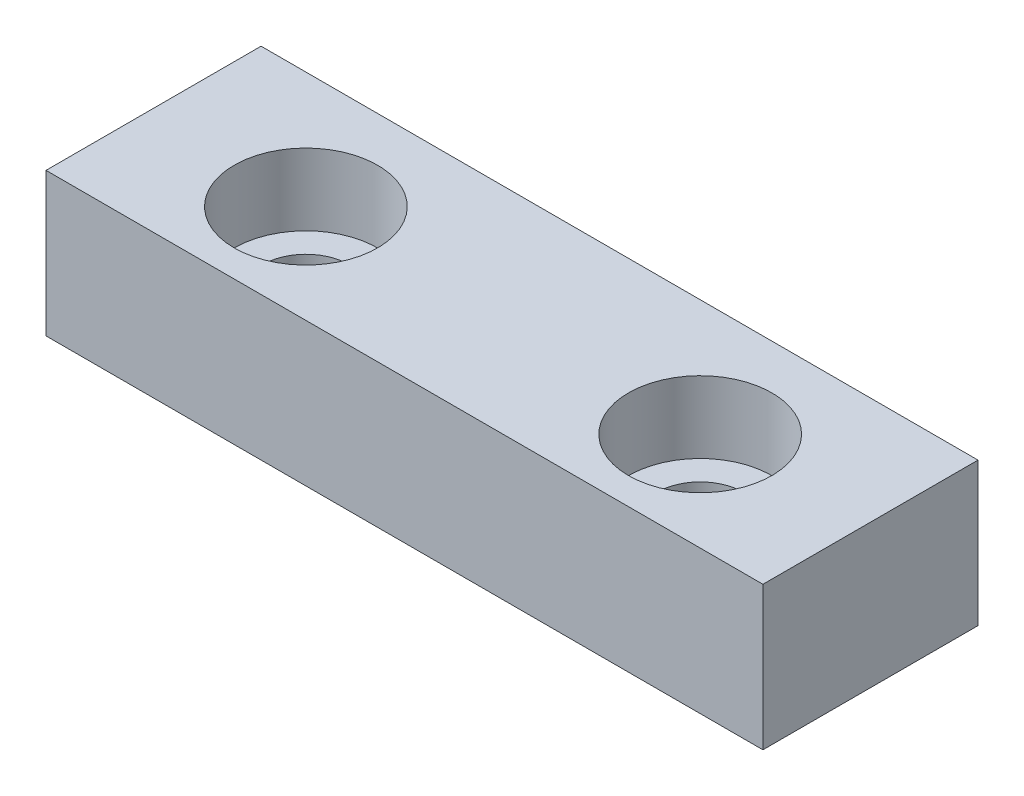
SolidWorks part; units mm, degrees
material "SKD11淬火HRC56-60"
ref_plane "前基準面" through (0, 0, 0) normal (0, 0, 1) x (1, 0, 0)
ref_plane "上基準面" through (0, 0, 0) normal (0, 1, 0) x (1, 0, 0)
ref_plane "右基準面" through (0, 0, 0) normal (1, 0, 0) x (0, 0, -1)
sketch "草图1" plane through (0, 0, 0) normal (0, 0, 1) x (1, 0, 0)
  line L1 (0, 0) -> (40, 0)
  line L2 (0, 0) -> (0, 8)
  line L3 (0, 8) -> (40, 8)
  line L4 (40, 0) -> (40, 8)
  dimension "D1" = 8
  dimension "D2" = 40
extrude "凸台-拉伸1" add sketch "草图1" along normal blind 12
hole_wizard "M4 六角凹头螺钉的柱形沉头孔3" positions "草图3" profile "草图2" counterbore size "M4" standard "ISO" end condition through all
sketch "草图3" plane through (0, 8, 0) normal (0, 1, 0) x (-1, 0, 0)
  line L0 (0, 6) -> (-40, 6) construction
  line L1 (0, 12) -> (0, 0) construction
  line L2 (-40, 12) -> (-40, 0) construction
  line L3 (-20, 0) -> (-20, 12) construction
  line L4 (-40, 0) -> (0, 0) construction
  line L5 (-40, 12) -> (0, 12) construction
  point P0 (-9, 6.5)
  point P1 (-31, 6.5)
  dimension "D1" = 22
  dimension "D2" = 5.5
sketch "草图2" plane through (9, 8, 6.5) normal (1, 0, 0) x (0, 0, 1)
  line L0 (0, 0) -> (0, 8)
  line L1 (0, 8) -> (2.4, 8)
  line L3 (2.4, 8) -> (2.4, 4)
  line L4 (2.4, 4) -> (4, 4)
  line L5 (4, 4) -> (4, 0)
  line L7 (4, 0) -> (0, 0)
  line L11 (0, -6.35) -> (0, 107.95) construction
  dimension "通孔孔直径" = 4.8
  dimension "通孔孔深度" = 8
  dimension "柱形沉头孔直径" = 8
  dimension "柱形沉头孔深度" = 4
